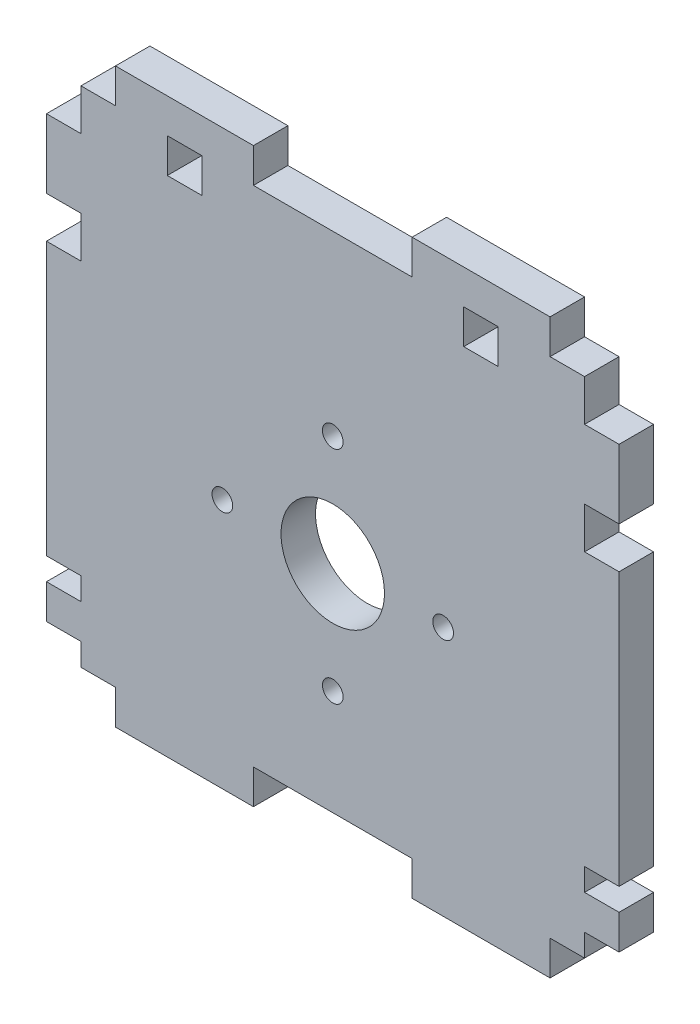
SolidWorks part; units mm, degrees
ref_plane "Plan de face" through (0, 0, 0) normal (0, 0, 1) x (1, 0, 0)
ref_plane "Plan de dessus" through (0, 0, 0) normal (0, 1, 0) x (1, 0, 0)
ref_plane "Plan de droite" through (0, 0, 0) normal (1, 0, 0) x (0, 0, -1)
sketch "Esquisse1" plane through (0, 0, 0) normal (0, 0, 1) x (1, 0, 0)
  line L1 (0, 0) -> (83, 0)
  line L2 (0, 0) -> (0, 73)
  line L3 (0, 73) -> (83, 73)
  line L4 (83, 0) -> (83, 73)
  circle A0 centre (41.5, 31.275) radius 7.5
  dimension "D2" = 15
  dimension "D1" = 31.275
  dimension "D3" = 83
  dimension "D4" = 73
  dimension "D5" = 41.5
extrude "Boss.-Extru.1" add sketch "Esquisse1" along normal blind 5
sketch "Esquisse2" plane through (0, 0, 5) normal (0, 0, 1) x (1, 0, 0)
  line L0 (83, 0) -> (83, 73) construction
  line L1 (78, 67) -> (83, 67)
  line L2 (78, 67) -> (78, 73)
  line L3 (78, 73) -> (83, 73)
  line L4 (83, 67) -> (83, 73)
  line L5 (78, 57) -> (83, 57)
  line L6 (78, 57) -> (78, 51)
  line L7 (78, 51) -> (83, 51)
  line L8 (83, 57) -> (83, 51)
  line L9 (83, 51) -> (78, 51) construction
  line L10 (78, 8.25) -> (83, 8.25) construction
  line L11 (78, 3.25) -> (83, 3.25)
  line L12 (78, 3.25) -> (78, 0)
  line L13 (78, 0) -> (83, 0)
  line L14 (83, 3.25) -> (83, 0)
  line L15 (78, 11.5) -> (83, 11.5)
  line L16 (78, 11.5) -> (78, 8.25)
  line L17 (78, 8.25) -> (83, 8.25)
  line L18 (83, 11.5) -> (83, 8.25)
  line L19 (41.5, 73) -> (41.5, 0) construction
  line L20 (83, 73) -> (0, 73) construction
  line L21 (0, 0) -> (83, 0) construction
  line L22 (0, 11.5) -> (0, 8.25)
  line L23 (5, 8.25) -> (0, 8.25)
  line L24 (5, 11.5) -> (5, 8.25)
  line L25 (5, 11.5) -> (0, 11.5)
  line L26 (0, 3.25) -> (0, 0)
  line L27 (5, 0) -> (0, 0)
  line L28 (5, 3.25) -> (5, 0)
  line L29 (5, 3.25) -> (0, 3.25)
  line L30 (0, 57) -> (0, 51)
  line L31 (5, 51) -> (0, 51)
  line L32 (5, 57) -> (5, 51)
  line L33 (5, 57) -> (0, 57)
  line L34 (0, 67) -> (0, 73)
  line L35 (5, 73) -> (0, 73)
  line L36 (5, 67) -> (5, 73)
  line L37 (5, 67) -> (0, 67)
  line L38 (17.5167, 68) -> (17.5167, 73)
  line L39 (60.4833, 68) -> (65.4833, 68)
  line L40 (60.4833, 68) -> (60.4833, 73)
  line L41 (60.4833, 73) -> (65.4833, 73)
  line L42 (65.4833, 68) -> (65.4833, 73)
  line L43 (22.5167, 73) -> (17.5167, 73)
  line L44 (22.5167, 68) -> (22.5167, 73)
  line L45 (22.5167, 68) -> (17.5167, 68)
  circle A0 centre (41.5, 47.275) radius 1.5
  circle A1 centre (25.5, 31.275) radius 1.5
  circle A2 centre (57.5, 31.275) radius 1.5
  circle A3 centre (41.5, 15.275) radius 1.5
  dimension "D1" = 5
extrude "Enlèv. mat.-Extru.1" cut sketch "Esquisse2" against normal blind 5
sketch "Esquisse3" plane through (0, 0, 5) normal (0, 0, 1) x (1, 0, 0)
  line L0 (78, 73) -> (65.4833, 73) construction
  line L1 (73, 73) -> (53, 73)
  line L2 (73, 73) -> (73, 78)
  line L3 (73, 78) -> (53, 78)
  line L4 (53, 73) -> (53, 78)
  line L5 (41.5, 73) -> (41.5, 0) construction
  line L6 (60.4833, 73) -> (22.5167, 73) construction
  line L7 (5, 0) -> (78, 0) construction
  line L8 (83, 57) -> (83, 67) construction
  line L9 (30, 73) -> (30, 78)
  line L10 (10, 78) -> (30, 78)
  line L11 (10, 73) -> (10, 78)
  line L12 (10, 73) -> (30, 73)
  line L13 (53, 0) -> (53, -5)
  line L14 (10, 0) -> (30, 0)
  line L15 (10, 0) -> (10, -5)
  line L16 (10, -5) -> (30, -5)
  line L17 (30, 0) -> (30, -5)
  line L18 (73, -5) -> (53, -5)
  line L19 (73, 0) -> (73, -5)
  line L20 (73, 0) -> (53, 0)
  dimension "D1" = 5
  dimension "D2" = 10
  dimension "D3" = 20
  dimension "D4" = 5
  dimension "D5" = 23
  dimension "D6" = 20
extrude "Boss.-Extru.2" add sketch "Esquisse3" against normal blind 5
